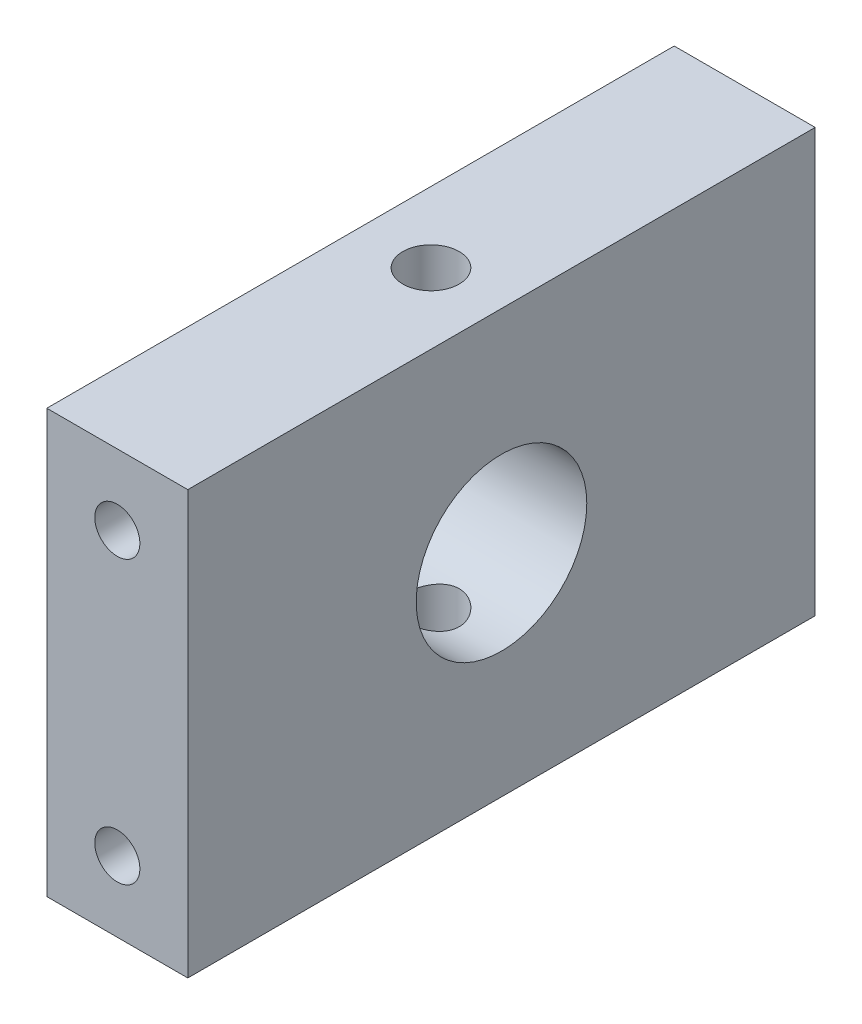
SolidWorks part; units mm, degrees
material "1060 合金"
ref_plane "正面" through (0, 0, 0) normal (0, 0, 1) x (1, 0, 0)
ref_plane "平面" through (0, 0, 0) normal (0, 1, 0) x (1, 0, 0)
ref_plane "右側面" through (0, 0, 0) normal (1, 0, 0) x (0, 0, -1)
sketch "ｽｹｯﾁ1" plane through (0, 0, 0) normal (1, 0, 0) x (0, 0, -1)
  line L1 (-22.25, 15) -> (22.25, 15)
  line L2 (-22.25, 15) -> (-22.25, -15)
  line L3 (-22.25, -15) -> (22.25, -15)
  line L4 (22.25, 15) -> (22.25, -15)
  line L5 (-22.25, 15) -> (22.25, -15) construction
  line L6 (-22.25, -15) -> (22.25, 15) construction
  circle A0 centre (0, 0) radius 6.05
  dimension "D1" = 12.1
  dimension "D2" = 44.5
  dimension "D3" = 30
extrude "ﾎﾞｽ - 押し出し1" add sketch "ｽｹｯﾁ1" along normal blind 10
sketch "ｽｹｯﾁ2" plane through (0, 0, 22.25) normal (0, 0, 1) x (1, 0, 0)
  line L0 (0, 0) -> (10, 0) construction
  line L1 (10, 15) -> (10, -15) construction
  line L2 (5, 0) -> (5, 10) construction
  circle A0 centre (5, 10) radius 1.6
  circle A1 centre (5, -10) radius 1.6
  dimension "D1" = 3.2
  dimension "D2" = 20
extrude "ｶｯﾄ - 押し出し1" cut sketch "ｽｹｯﾁ2" against normal blind 10
sketch "ｽｹｯﾁ3" plane through (0, 15, 0) normal (0, 1, 0) x (1, 0, 0)
  line L0 (0, 0) -> (10, 0) construction
  line L1 (10, 22.25) -> (10, -22.25) construction
  circle A0 centre (5, 0) radius 2
  dimension "D1" = 4
extrude "ｶｯﾄ - 押し出し2" cut sketch "ｽｹｯﾁ3" against normal through all
ref_plane "平面1" through (0, 0, 0) normal (0, 0, 1) x (1, 0, 0)
mirror "ﾐﾗｰ1" about plane through (0, 0, 0) normal (0, 0, 1) of "ｶｯﾄ - 押し出し1"
